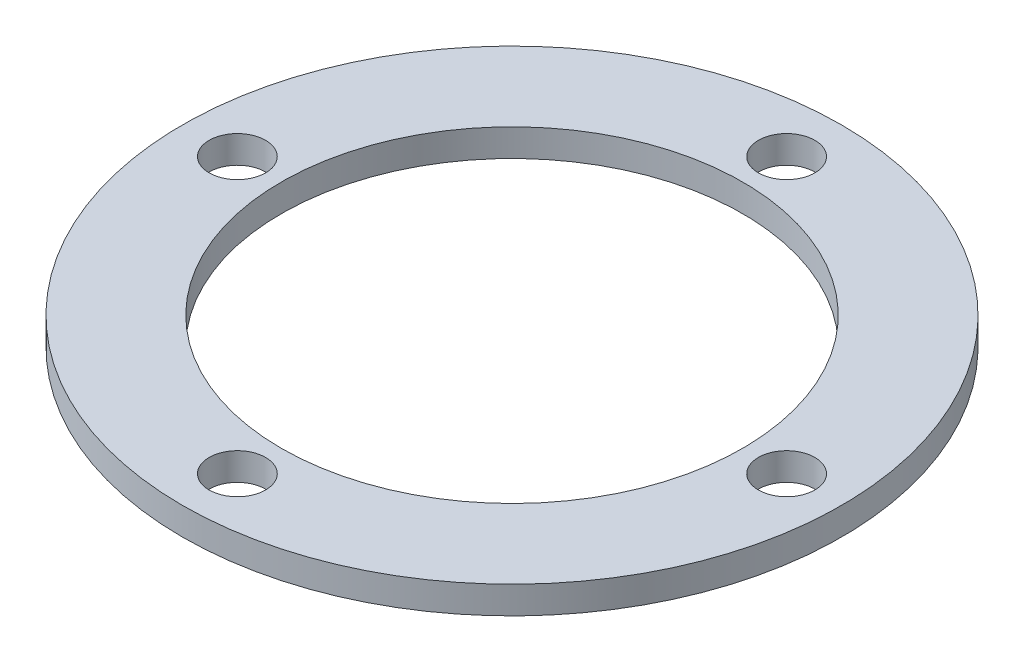
SolidWorks part; units mm, degrees
ref_plane "Front Plane" through (0, 0, 0) normal (0, 0, 1) x (1, 0, 0)
ref_plane "Top Plane" through (0, 0, 0) normal (0, 1, 0) x (1, 0, 0)
ref_plane "Right Plane" through (0, 0, 0) normal (1, 0, 0) x (0, 0, -1)
sketch "Sketch1" plane through (0, 0, 0) normal (0, 1, 0) x (1, 0, 0)
  circle A0 centre (0, 0) radius 38.1
  circle A1 centre (0, 0) radius 26.67
  circle A2 centre (0, 31.75) radius 3.2639
  circle A3 centre (31.75, 0) radius 3.2639
  circle A4 centre (0, -31.75) radius 3.2639
  circle A5 centre (-31.75, 0) radius 3.2639
  point P6 (0, 0)
  point P7 (0, 0)
  point P15 (0, 0)
  dimension "D1" = 76.2
  dimension "D2" = 53.34
  dimension "D4" = 6.5278
  dimension "D3" = 31.75
  dimension "D5" = 4
extrude "Boss-Extrude1" add sketch "Sketch1" along normal blind 3.175
